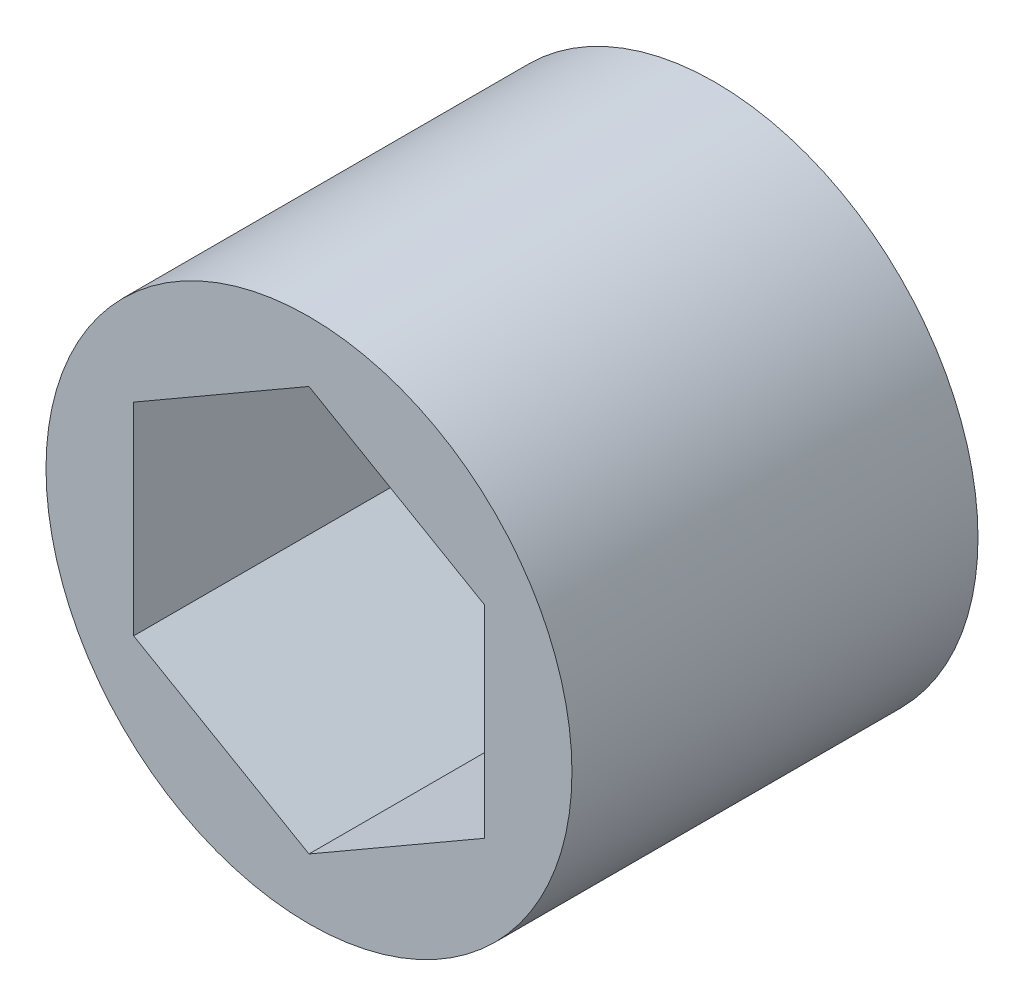
SolidWorks part; units mm, degrees
material "Nylon 101"
ref_plane "Front Plane" through (0, 0, 0) normal (0, 0, 1) x (1, 0, 0)
ref_plane "Top Plane" through (0, 0, 0) normal (0, 1, 0) x (1, 0, 0)
ref_plane "Right Plane" through (0, 0, 0) normal (1, 0, 0) x (0, 0, -1)
sketch "Sketch1" plane through (0, 0, 0) normal (0, 0, 1) x (1, 0, 0)
  line L1 (0, 7.3323) -> (-6.35, 3.6662)
  line L2 (-6.35, 3.6662) -> (-6.35, -3.6662)
  line L3 (-6.35, -3.6662) -> (0, -7.3323)
  line L4 (0, -7.3323) -> (6.35, -3.6662)
  line L5 (6.35, -3.6662) -> (6.35, 3.6662)
  line L6 (6.35, 3.6662) -> (0, 7.3323)
  circle A0 centre (0, 0) radius 6.35 construction
  circle A1 centre (0, 0) radius 9.525
  dimension "D1" = 19.05
  dimension "D2" = 12.7
extrude "Boss-Extrude1" add sketch "Sketch1" along normal mid plane 14.7066
